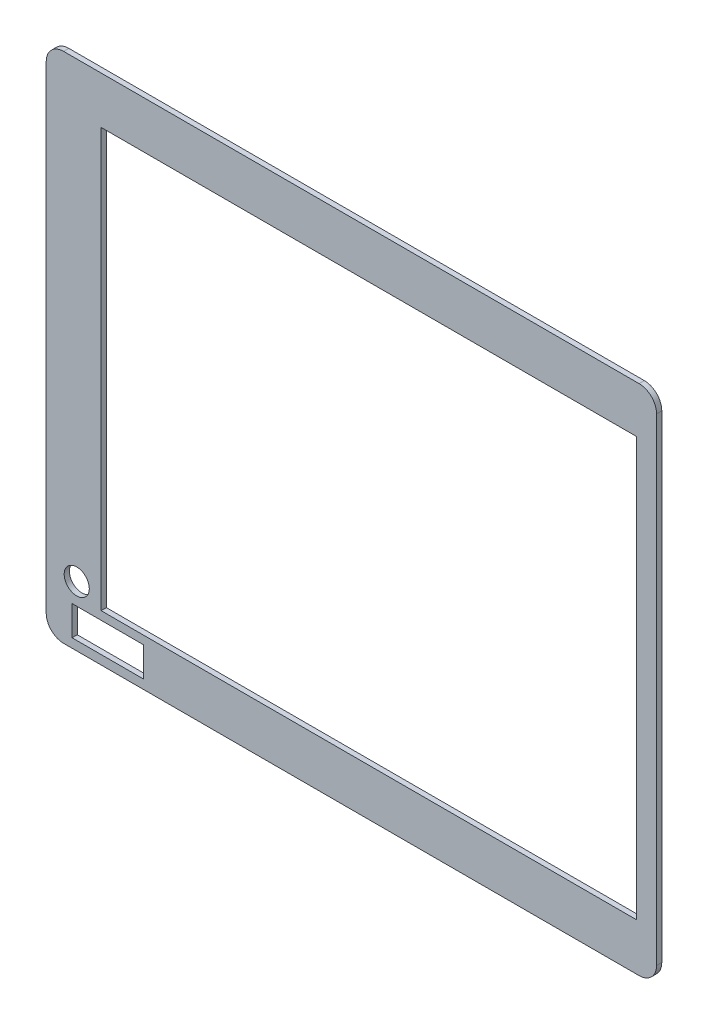
SolidWorks part; units mm, degrees
ref_plane "Front Plane" through (0, 0, 0) normal (0, 0, 1) x (1, 0, 0)
ref_plane "Top Plane" through (0, 0, 0) normal (0, 1, 0) x (1, 0, 0)
ref_plane "Right Plane" through (0, 0, 0) normal (1, 0, 0) x (0, 0, -1)
sketch "Sketch1" plane through (0, 0, 0) normal (0, 0, 1) x (1, 0, 0)
  line L1 (-350, -294) -> (350, -294)
  line L2 (-350, -294) -> (-350, 294)
  line L3 (-350, 294) -> (350, 294)
  line L4 (350, -294) -> (350, 294)
  line L5 (-350, -294) -> (350, 294) construction
  line L6 (-350, 294) -> (350, -294) construction
  point P0 (0, 0)
  dimension "D1" = 588
  dimension "D2" = 700
extrude "Boss-Extrude1" add sketch "Sketch1" along normal blind 6
fillet "Fillet1" radius 20 4 edges at (-350, 294, 3) (350, 294, 3) (350, -294, 3) (-350, -294, 3)
sketch "Sketch2" plane through (0, 0, 6) normal (0, 0, 1) x (1, 0, 0)
  line L0 (-350, 274) -> (-350, -274) construction
  line L138 (330, 294) -> (-330, 294) construction
  line L139 (-330, -294) -> (330, -294) construction
  line L144 (-315, -279) -> (-243.7, -279)
  line L151 (-315, -279) -> (-315, -254.6)
  line L152 (-315, -254.6) -> (-243.7, -254.6)
  line L153 (-243.7, -279) -> (-243.7, -254.6)
  line L163 (188.4646, -283.6) -> (311, -283.6)
  line L165 (-287, -240) -> (327, -240)
  line L166 (-287, -240) -> (-287, 240)
  line L167 (-287, 240) -> (327, 240)
  line L168 (-320.35, -283.6) -> (-238.35, -283.6)
  line L169 (-320.35, -283.6) -> (-320.35, -249.6)
  line L170 (-320.35, -249.6) -> (-238.35, -249.6)
  line L171 (-238.35, -283.6) -> (-238.35, -249.6)
  line L172 (-320.35, -283.6) -> (-238.35, -249.6) construction
  line L173 (-320.35, -249.6) -> (-238.35, -283.6) construction
  line L174 (327, -240) -> (327, 240)
  circle A79 centre (-315, -225) radius 14.4
  text T2 "Masteroppgave Emil Aasen Skogheim" font "Century Gothic" height in points 16
  point P226 (-279.35, -266.6)
  dimension "D26" = 71.3
  dimension "D27" = 15
  dimension "D28" = 12
  dimension "D31" = 35.65
  dimension "D30" = 28.8
  dimension "D20" = 24.4
  dimension "D32" = 35
  dimension "D33" = 82
  dimension "D34" = 34
extrude "Cut-Extrude1" cut sketch "Sketch2" against normal blind 84 contours L166 L167 L174 L165 | L170 L171 L168 L169 | A79
